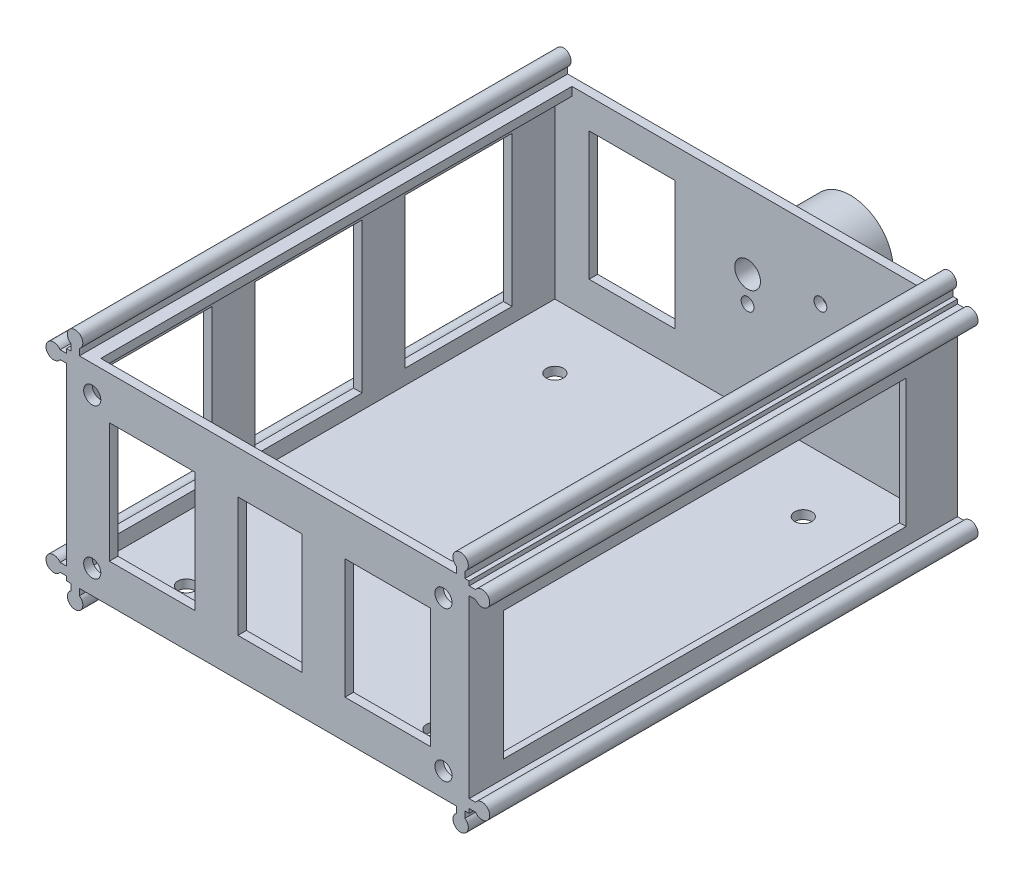
SolidWorks part; units mm, degrees
ref_plane "前视基准面" through (0, 0, 0) normal (0, 0, 1) x (1, 0, 0)
ref_plane "上视基准面" through (0, 0, 0) normal (0, 1, 0) x (1, 0, 0)
ref_plane "右视基准面" through (0, 0, 0) normal (1, 0, 0) x (0, 0, -1)
sketch "草图1" plane through (0, 0, 0) normal (0, 1, 0) x (1, 0, 0)
  line L1 (0, 0) -> (100, 0)
  line L2 (0, 0) -> (0, 130)
  line L3 (0, 130) -> (100, 130)
  line L4 (100, 0) -> (100, 130)
  circle A0 centre (15, 105) radius 2
  circle A1 centre (15, 19) radius 2
  circle A2 centre (73, 105) radius 2
  circle A3 centre (73, 19) radius 2
  dimension "D6" = 4
  dimension "D7" = 4
  dimension "D8" = 4
  dimension "D9" = 4
  dimension "D1" = 130
  dimension "D2" = 100
  dimension "D3" = 86
  dimension "D4" = 86
  dimension "D5" = 58
  dimension "D10" = 15
  dimension "D11" = 25
extrude "凸台-拉伸1" add sketch "草图1" along normal blind 2
sketch "草图3" plane through (0, 2, 0) normal (0, 1, 0) x (1, 0, 0)
  line L5 (0, 122) -> (0, 120)
  line L6 (100, 120) -> (0, 120)
  line L7 (100, 122) -> (100, 120)
  line L8 (100, 122) -> (0, 122)
  line L9 (100, 65) -> (6.6451, 65) construction
  line L10 (100, 8) -> (0, 8)
  line L11 (100, 8) -> (100, 10)
  line L12 (100, 10) -> (0, 10)
  line L13 (0, 8) -> (0, 10)
  line L18 (100, 0) -> (100, 130) construction
  line L20 (0, 130) -> (0, 0) construction
  dimension "D1" = 110
  dimension "D2" = 2
extrude "凸台-拉伸2" add sketch "草图3" along normal blind 45
sketch "草图4" plane through (0, 2, 0) normal (0, 1, 0) x (1, 0, 0)
  line L0 (0, 120) -> (100, 120) construction
  line L1 (90.5, 120) -> (92, 120)
  line L2 (90.5, 120) -> (90.5, 10)
  line L3 (90.5, 10) -> (92, 10)
  line L4 (92, 120) -> (92, 10)
  line L5 (100, 10) -> (0, 10) construction
  line L6 (100, 10) -> (100, 120) construction
  dimension "D1" = 8
  dimension "D2" = 1.5
extrude "凸台-拉伸3" add sketch "草图4" along normal blind 5
sketch "草图5" plane through (0, 0, 0) normal (-1, 0, 0) x (0, 0, 1)
  line L0 (-8, 47) -> (-8, 2) construction
  line L1 (-122, 47) -> (-8, 47)
  line L2 (-122, 47) -> (-122, 0)
  line L3 (-122, 0) -> (-8, 0)
  line L4 (-8, 47) -> (-8, 0)
  line L5 (-130, 0) -> (0, 0) construction
extrude "凸台-拉伸7" add sketch "草图5" along normal blind 2 contours L1 L4 L3 L2
sketch "草图6" plane through (0, 2, 0) normal (0, 1, 0) x (1, 0, 0)
  line L0 (92, 10) -> (92, 120) construction
  line L1 (0, 8) -> (92, 8)
  line L2 (0, 8) -> (0, 0)
  line L3 (0, 0) -> (100, 0)
  line L4 (100, 13) -> (100, 0)
  line L5 (0, 122) -> (92, 122)
  line L6 (0, 122) -> (0, 130)
  line L7 (0, 130) -> (100, 130)
  line L8 (100, 117) -> (100, 130)
  line L10 (100, 13) -> (100, 117)
  line L12 (92, 8) -> (92, 122)
extrude "切除-拉伸3" cut sketch "草图6" against normal through all and the other way through all
sketch "草图11" plane through (92, 0, 0) normal (1, 0, 0) x (0, 0, -1)
  line L0 (122, 0) -> (122, 47) construction
  line L1 (8, 47) -> (122, 47)
  line L3 (16, 37) -> (110, 37)
  line L4 (122, 47) -> (122, 42)
  line L5 (16, 37) -> (16, 0)
  line L6 (122, 0) -> (110, 0)
  line L7 (122, 0) -> (122, 42)
  line L9 (110, 0) -> (110, 37)
  line L10 (122, 0) -> (8, 0) construction
  line L11 (16, 0) -> (8, 0)
  line L12 (8, 47) -> (8, 0)
  dimension "D1" = 5
  dimension "D2" = 12
  dimension "D3" = 10
  dimension "D4" = 8
extrude "凸台-拉伸10" add sketch "草图11" against normal blind 1.5
sketch "草图12" plane through (0, 0, -8) normal (0, 0, 1) x (1, 0, 0)
  line L0 (91, 47) -> (91, 48.5)
  line L1 (92, 47) -> (91, 47)
  line L2 (92, 47) -> (92, 46)
  line L3 (90, 45) -> (86, 45)
  line L4 (86, 47) -> (86, 45)
  line L5 (90, 49.9967) -> (90, 36.8759) construction
  line L6 (89, 47) -> (89, 48.5)
  line L7 (89, 47) -> (86, 47)
  line L8 (45, 47) -> (45, 12.8789) construction
  line L9 (-2, 47) -> (92, 47) construction
  line L17 (-2, 23.5) -> (92, 23.5) construction
  line L18 (-2, 47) -> (-2, 0) construction
  line L19 (92, 0) -> (92, 47) construction
  line L34 (94.9967, 45) -> (87.3674, 45) construction
  line L35 (93.5, 46) -> (92, 46)
  line L36 (94.9967, 45) -> (92.4381, 45) construction
  line L37 (93.5, 44) -> (92, 44)
  line L38 (92, 44) -> (92, 42.3188)
  line L39 (92, 0) -> (92, 47) construction
  line L40 (92, 42.3188) -> (90, 42.3188)
  line L41 (90, 42.3188) -> (90, 45)
  line L42 (-4.9967, 45) -> (-2.4381, 45) construction
  line L43 (-4.9967, 45) -> (2.6326, 45) construction
  line L44 (0, 42.3188) -> (0, 45)
  line L45 (-2, 42.3188) -> (0, 42.3188)
  line L46 (-2, 44) -> (-2, 42.3188)
  line L47 (-3.5, 44) -> (-2, 44)
  line L48 (-3.5, 46) -> (-2, 46)
  line L49 (1, 47) -> (4, 47)
  line L50 (1, 47) -> (1, 48.5)
  line L51 (4, 47) -> (4, 45)
  line L52 (0, 45) -> (4, 45)
  line L53 (-2, 47) -> (-2, 46)
  line L54 (-2, 47) -> (-1, 47)
  line L55 (-1, 47) -> (-1, 48.5)
  line L56 (-4.9967, 2) -> (2.6326, 2) construction
  line L57 (-4.9967, 2) -> (-2.4381, 2) construction
  line L58 (-1, 0) -> (-1, -1.5)
  line L59 (-2, 0) -> (-1, 0)
  line L60 (-2, 0) -> (-2, 1)
  line L61 (0, 2) -> (4, 2)
  line L62 (4, 0) -> (4, 2)
  line L63 (1, 0) -> (1, -1.5)
  line L64 (1, 0) -> (4, 0)
  line L65 (-3.5, 1) -> (-2, 1)
  line L66 (-3.5, 3) -> (-2, 3)
  line L67 (-2, 3) -> (-2, 4.6812)
  line L68 (-2, 4.6812) -> (0, 4.6812)
  line L69 (0, 4.6812) -> (0, 2)
  line L70 (94.9967, 2) -> (92.4381, 2) construction
  line L71 (94.9967, 2) -> (87.3674, 2) construction
  line L72 (90, -2.9967) -> (90, 10.1241) construction
  line L73 (90, 4.6812) -> (90, 2)
  line L74 (92, 4.6812) -> (90, 4.6812)
  line L75 (92, 3) -> (92, 4.6812)
  line L76 (93.5, 3) -> (92, 3)
  line L77 (93.5, 1) -> (92, 1)
  line L78 (89, 0) -> (86, 0)
  line L79 (89, 0) -> (89, -1.5)
  line L80 (86, 0) -> (86, 2)
  line L81 (90, 2) -> (86, 2)
  line L82 (92, 0) -> (92, 1)
  line L83 (92, 0) -> (91, 0)
  line L84 (91, 0) -> (91, -1.5)
  line L85 (-2, 47) -> (-2, 0) construction
  arc A0 (91, 48.5) -> (89, 48.5) centre (90, 49.9967) ccw
  arc A4 (93.5, 44) -> (93.5, 46) centre (94.9967, 45) ccw
  arc A5 (-3.5, 44) -> (-3.5, 46) centre (-4.9967, 45) cw
  arc A6 (-1, 48.5) -> (1, 48.5) centre (0, 49.9967) cw
  arc A7 (-1, -1.5) -> (1, -1.5) centre (0, -2.9967) ccw
  arc A8 (-3.5, 3) -> (-3.5, 1) centre (-4.9967, 2) ccw
  arc A9 (93.5, 3) -> (93.5, 1) centre (94.9967, 2) cw
  arc A10 (91, -1.5) -> (89, -1.5) centre (90, -2.9967) cw
  dimension "D3" = 1.8
  dimension "D7" = 3.6
  dimension "D1" = 2
  dimension "D2" = 6
  dimension "D4" = 2
  dimension "D5" = 1.5
  dimension "D6" = 2
  dimension "D8" = 2
  dimension "D9" = 1.5
extrude "凸台-拉伸11" add sketch "草图12" against normal through all
sketch "草图13" plane through (0, 0, -8) normal (0, 0, 1) x (1, 0, 0)
  line L0 (45, 47) -> (45, -0.801) construction
  line L1 (1, 47) -> (89, 47) construction
  line L3 (45, 23.0995) -> (95.0713, 23.0995) construction
  circle A0 centre (86, 40.5995) radius 2
  circle A1 centre (86, 5.5995) radius 2
  circle A2 centre (4, 5.5995) radius 2
  circle A3 centre (4, 40.5995) radius 2
  point P4 (45, -0.801)
  dimension "D2" = 35
  dimension "D3" = 4
  dimension "D1" = 82
extrude "切除-拉伸4" cut sketch "草图13" against normal up to next
sketch "草图14" plane through (0, 0, -122) normal (0, 0, -1) x (-1, 0, 0)
  line L0 (-92, 23.5) -> (2, 23.5) construction
  line L1 (-92, 3) -> (-92, 44) construction
  line L2 (2, 44) -> (2, 3) construction
  line L3 (-45, 47) -> (-45, 0) construction
  line L4 (-89, 47) -> (-1, 47) construction
  line L5 (-1, 0) -> (-89, 0) construction
  circle A0 centre (-45, 23.5) radius 10
  dimension "D1" = 20
extrude "凸台-拉伸12" add sketch "草图14" along normal blind 22
sketch "草图15" plane through (0, 0, -122) normal (0, 0, -1) x (-1, 0, 0)
  line L0 (-92, 3) -> (-92, 44) construction
  line L1 (-89, 47) -> (-1, 47) construction
  circle A0 centre (-62, 32) radius 1.5
  circle A1 centre (-62, 15) radius 1.5
  dimension "D2" = 3
  dimension "D3" = 3
  dimension "D1" = 17
  dimension "D4" = 30
  dimension "D5" = 15
extrude "切除-拉伸5" cut sketch "草图15" against normal up to next
sketch "草图16" plane through (0, 0, -144) normal (0, 0, -1) x (-1, 0, 0)
  circle A0 centre (-45, 23.5) radius 1.5
  dimension "D1" = 3
extrude "切除-拉伸6" cut sketch "草图16" against normal up to next
sketch "草图17" plane through (-2, 0, 0) normal (-1, 0, 0) x (0, 0, 1)
  line L0 (-122, 44) -> (-122, 3) construction
  line L1 (-110, 5.5) -> (-85, 5.5)
  line L2 (-110, 5.5) -> (-110, 40.5)
  line L3 (-110, 40.5) -> (-85, 40.5)
  line L4 (-85, 5.5) -> (-85, 40.5)
  line L5 (-75, 5.5) -> (-50, 5.5)
  line L6 (-75, 5.5) -> (-75, 40.5)
  line L7 (-75, 40.5) -> (-50, 40.5)
  line L8 (-50, 5.5) -> (-50, 40.5)
  line L9 (-40, 5.5) -> (-15, 5.5)
  line L10 (-40, 5.5) -> (-40, 40.5)
  line L11 (-40, 40.5) -> (-15, 40.5)
  line L12 (-15, 5.5) -> (-15, 40.5)
  line L13 (-122, 23.5) -> (0, 23.5) construction
  dimension "D1" = 35
  dimension "D2" = 10
  dimension "D3" = 10
  dimension "D4" = 12
  dimension "D5" = 25
  dimension "D6" = 25
  dimension "D7" = 25
  dimension "D8" = 17
extrude "切除-拉伸7" cut sketch "草图17" against normal up to next
sketch "草图18" plane through (0, 0, -122) normal (0, 0, -1) x (-1, 0, 0)
  line L0 (-1, 0) -> (-89, 0) construction
  line L1 (-8, 10) -> (-28, 10)
  line L2 (-8, 10) -> (-8, 40)
  line L3 (-8, 40) -> (-28, 40)
  line L4 (-28, 10) -> (-28, 40)
  line L5 (2, 44) -> (2, 3) construction
  dimension "D1" = 20
  dimension "D2" = 30
  dimension "D3" = 10
  dimension "D4" = 10
extrude "切除-拉伸8" cut sketch "草图18" against normal up to next
sketch "草图19" plane through (0, 0, -8) normal (0, 0, 1) x (1, 0, 0)
  line L0 (-2, 44) -> (-2, 3) construction
  line L1 (8, 37) -> (28, 37)
  line L2 (8, 37) -> (8, 9)
  line L3 (8, 9) -> (28, 9)
  line L4 (28, 37) -> (28, 9)
  line L5 (38, 37) -> (53, 37)
  line L6 (38, 37) -> (38, 9)
  line L7 (38, 9) -> (53, 9)
  line L8 (53, 37) -> (53, 9)
  line L9 (63, 37) -> (83, 37)
  line L10 (63, 37) -> (63, 9)
  line L11 (63, 9) -> (83, 9)
  line L12 (83, 37) -> (83, 9)
  line L13 (1, 47) -> (89, 47) construction
  dimension "D1" = 10
  dimension "D2" = 10
  dimension "D3" = 20
  dimension "D4" = 20
  dimension "D5" = 15
  dimension "D6" = 10
  dimension "D7" = 28
  dimension "D8" = 10
extrude "切除-拉伸9" cut sketch "草图19" against normal up to next
sketch "草图20" plane through (0, 0, -144) normal (0, 0, -1) x (-1, 0, 0)
  circle A0 centre (-45, 29.5) radius 3
  circle A2 centre (-45, 23.5) radius 1.5 construction
  point P2 (-45, 18.096)
  point P3 (-45, 29.7269)
  dimension "D1" = 6
  dimension "D2" = 6
extrude "切除-拉伸10" cut sketch "草图20" against normal up to next
